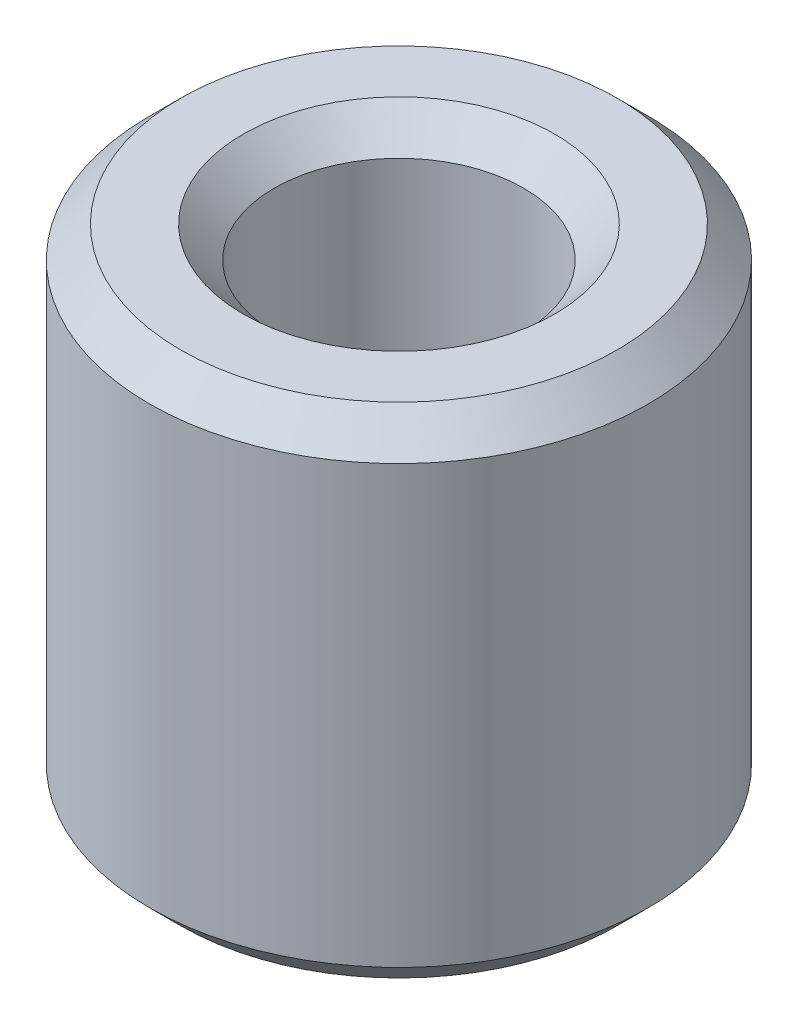
SolidWorks part; units mm, degrees
material "aluminio"
ref_plane "Alzado" through (0, 0, 0) normal (0, 0, 1) x (1, 0, 0)
ref_plane "Planta" through (0, 0, 0) normal (0, 1, 0) x (1, 0, 0)
ref_plane "Vista lateral" through (0, 0, 0) normal (1, 0, 0) x (0, 0, -1)
sketch "Croquis1" plane through (0, 0, 0) normal (0, 1, 0) x (1, 0, 0)
  circle A0 centre (0, 0) radius 4
  circle A1 centre (0, 0) radius 2
  dimension "D1" = 8
  dimension "D2" = 4
extrude "Saliente-Extruir1" add sketch "Croquis1" along normal blind 8
chamfer "Chaflán1" distance 0.5 angle 45 4 edges at (0, 8, 2) (0, 8, 4) (0, 0, 4) (0, 0, 2)
